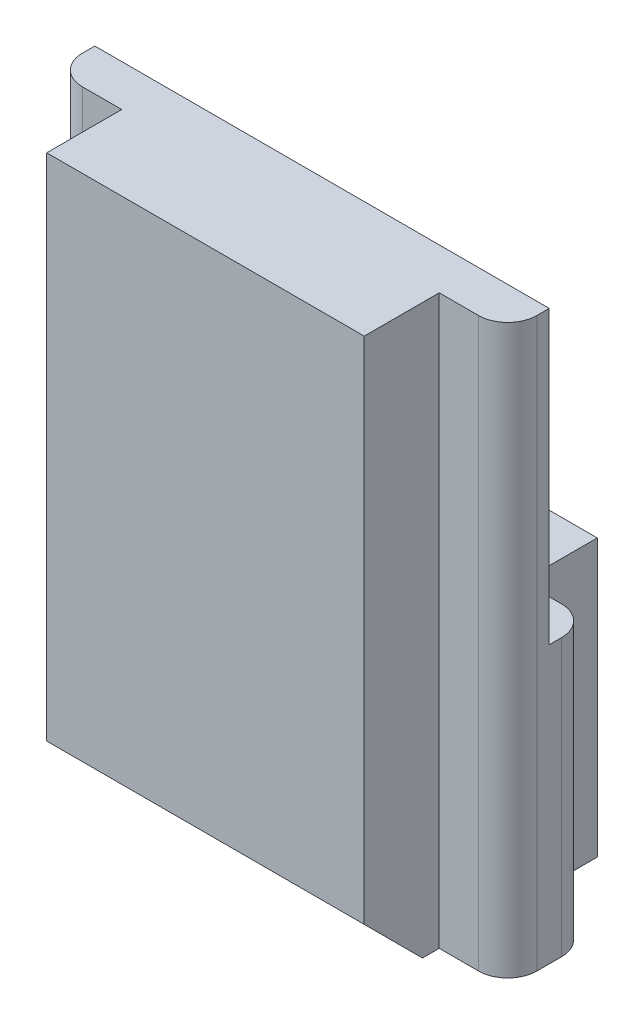
SolidWorks part; units mm, degrees
ref_plane "Plan de face" through (0, 0, 0) normal (0, 0, 1) x (1, 0, 0)
ref_plane "Plan de dessus" through (0, 0, 0) normal (0, 1, 0) x (1, 0, 0)
ref_plane "Plan de droite" through (0, 0, 0) normal (1, 0, 0) x (0, 0, -1)
sketch "Esquisse1" plane through (0, 0, 0) normal (0, 1, 0) x (1, 0, 0)
  line L0 (0, 4) -> (13.25, 4) construction
  line L1 (0, 0) -> (10.9, 0)
  line L2 (0, 0) -> (0, 8)
  line L3 (0, 8) -> (10.9, 8)
  line L4 (10.9, 0) -> (10.9, 8)
  line L6 (0, 2.575) -> (-2.35, 2.575)
  line L7 (0, 2.575) -> (0, 5.425)
  line L8 (0, 5.425) -> (-2.35, 5.425)
  line L9 (-2.35, 2.575) -> (-2.35, 5.425)
  line L10 (10.9, 2.575) -> (13.25, 2.575)
  line L11 (10.9, 2.575) -> (10.9, 5.425)
  line L12 (10.9, 5.425) -> (13.25, 5.425)
  line L13 (13.25, 2.575) -> (13.25, 5.425)
  dimension "D1" = 2.85
  dimension "D2" = 2.35
  dimension "D3" = 10.9
  dimension "D4" = 8
extrude "Boss.-Extru.1" add sketch "Esquisse1" along normal blind 19.49 contours L1 L4 L3 L2 | L6 L9 L8 L7 | L10 L13 L12 L11
chamfer "Chanfrein1" distance 2 angle 45 1 edges at (5.45, 0, 0)
sketch "Esquisse2" plane through (0, 19.49, 0) normal (0, 1, 0) x (1, 0, 0)
  line L0 (0, 0) -> (10.9, 0) construction
  line L1 (-2.35, 4) -> (13.25, 4)
  line L2 (-2.35, 4) -> (-2.35, 8)
  line L3 (-2.35, 8) -> (13.25, 8)
  line L4 (13.25, 4) -> (13.25, 8)
  line L5 (-2.35, 2.575) -> (-2.35, 5.425) construction
  line L6 (13.25, 2.575) -> (13.25, 5.425) construction
  line L7 (0, 8) -> (10.9, 8) construction
  dimension "D1" = 4
extrude "Enlèv. mat.-Extru.1" cut sketch "Esquisse2" against normal blind 10
fillet "Congé1" radius 1 4 edges at (13.25, 4.745, -5.425) (-2.35, 4.745, -5.425) (-2.35, 9.745, -2.575) (13.25, 9.745, -2.575)
